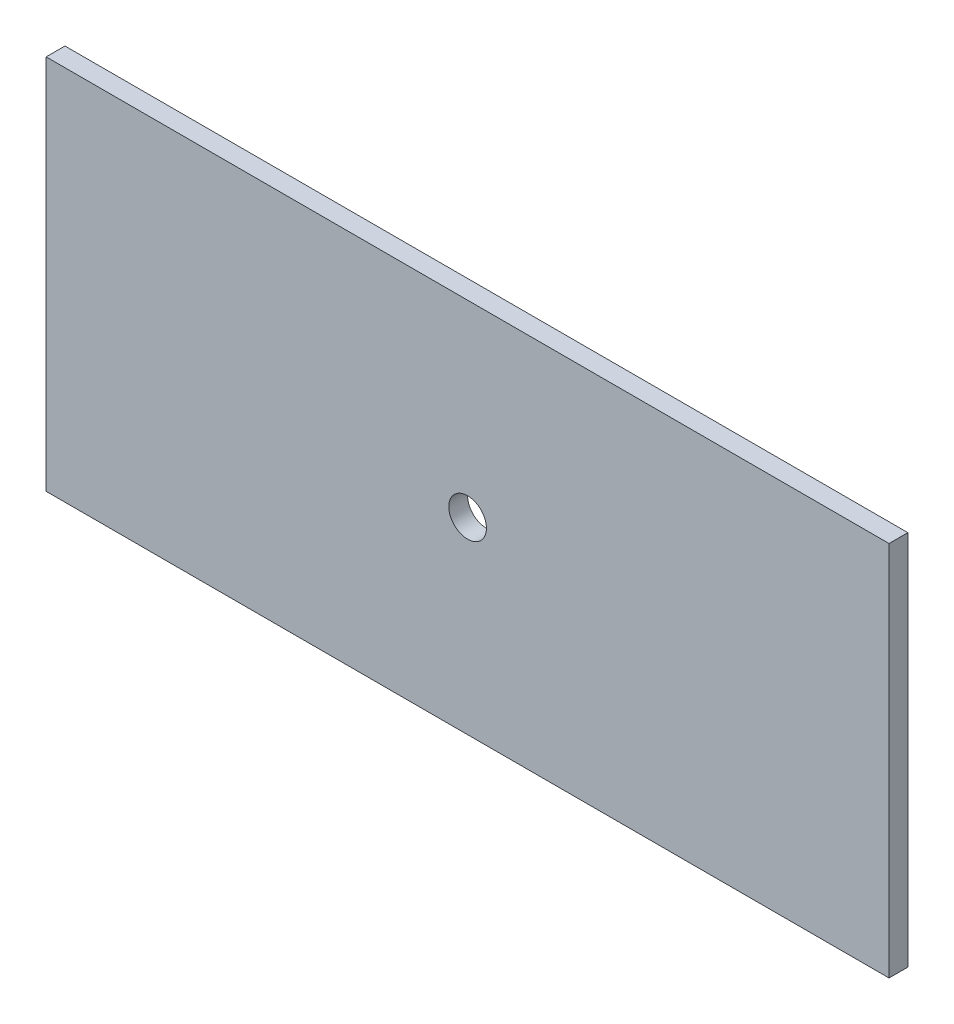
SolidWorks part; units mm, degrees
ref_plane "Front Plane" through (0, 0, 0) normal (0, 0, 1) x (1, 0, 0)
ref_plane "Top Plane" through (0, 0, 0) normal (0, 1, 0) x (1, 0, 0)
ref_plane "Right Plane" through (0, 0, 0) normal (1, 0, 0) x (0, 0, -1)
sketch "Sketch2" plane through (0, 0, 0) normal (0, 0, 1) x (1, 0, 0)
  line L1 (-142.24, -63.5) -> (142.24, -63.5)
  line L2 (-142.24, -63.5) -> (-142.24, 63.5)
  line L3 (-142.24, 63.5) -> (142.24, 63.5)
  line L4 (142.24, -63.5) -> (142.24, 63.5)
  line L5 (-142.24, -63.5) -> (142.24, 63.5) construction
  line L6 (-142.24, 63.5) -> (142.24, -63.5) construction
  point P0 (0, 0)
  dimension "D1" = 284.48
  dimension "D2" = 127
extrude "Boss-Extrude1" add sketch "Sketch2" along normal blind 6.35
sketch "Sketch3" plane through (0, 0, 6.35) normal (0, 0, 1) x (1, 0, 0)
  circle A0 centre (0, 0) radius 6.35
extrude "Cut-Extrude1" cut sketch "Sketch3" against normal through all
